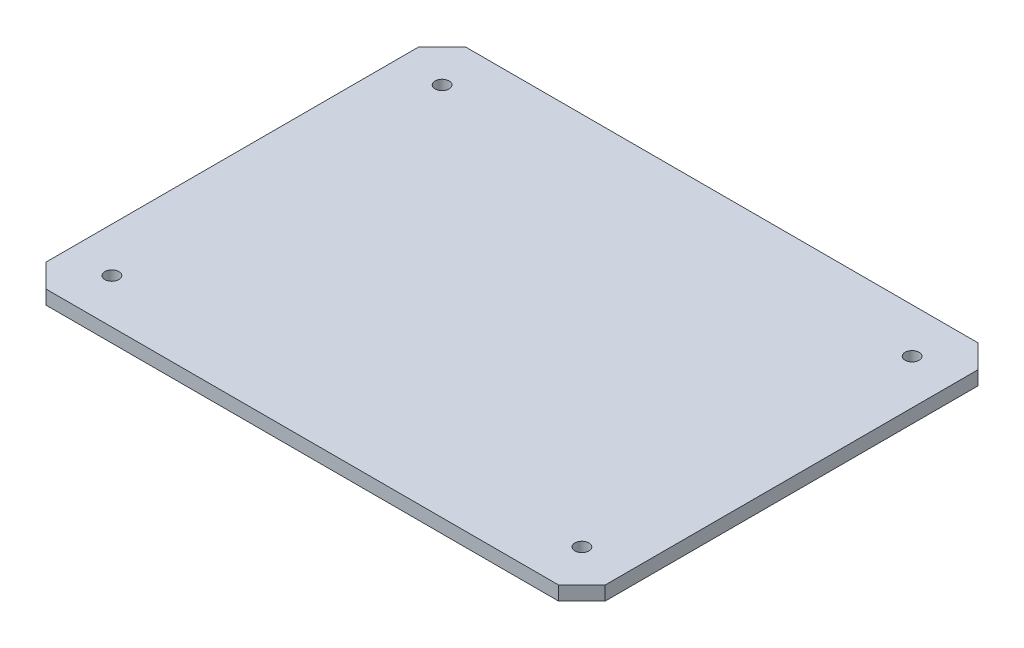
SolidWorks part; units mm, degrees
ref_plane "Front Plane" through (0, 0, 0) normal (0, 0, 1) x (1, 0, 0)
ref_plane "Top Plane" through (0, 0, 0) normal (0, 1, 0) x (1, 0, 0)
ref_plane "Right Plane" through (0, 0, 0) normal (1, 0, 0) x (0, 0, -1)
sketch "Sketch1" plane through (0, 0, 0) normal (0, 1, 0) x (1, 0, 0)
  line L1 (-60, 45) -> (60, 45)
  line L2 (-60, 45) -> (-60, -45)
  line L3 (-60, -45) -> (60, -45)
  line L4 (60, 45) -> (60, -45)
  line L5 (-60, 45) -> (60, -45) construction
  line L6 (-60, -45) -> (60, 45) construction
  point P0 (0, 0)
  dimension "D1" = 90
  dimension "D2" = 120
extrude "Boss-Extrude1" add sketch "Sketch1" along normal blind 3
chamfer "Chamfer1" distance 5 angle 45 4 edges at (-60, 1.5, 45) (-60, 1.5, -45) (60, 1.5, -45) (60, 1.5, 45)
sketch "Sketch5" plane through (0, 0, 0) normal (0, -1, 0) x (1, 0, 0)
  line L3 (-57.5, 42.5) -> (-6.9406, -8.0594) construction
  line L4 (-55, 45) -> (-60, 40) construction
  point P6 (-50.4289, 35.4289)
  point P16 (-52.9991, 39.1733)
  point P17 (-52.5503, 37.5503)
  dimension "D1" = 10
hole_wizard "Ø3.0 (3) Diameter Hole2" positions "Sketch5" profile "Sketch6" hole size "Ø3.0" standard "ANSI Metric" end condition through all
sketch "Sketch6" plane through (-50.4289, 0, 35.4289) normal (1, 0, 0) x (0, 0, -1)
  line L0 (0, 0) -> (0, 3)
  line L1 (0, 3) -> (1.5, 3)
  line L2 (1.5, 3) -> (1.5, 0)
  line L5 (1.5, 0) -> (0, 0)
  line L11 (0, -6.35) -> (0, 107.95) construction
  dimension "Thru Hole Dia." = 3
  dimension "Thru Hole Depth" = 3
mirror "Mirror1" about plane through (0, 0, 0) normal (0, 0, 1) of "Ø3.0 (3) Diameter Hole2" second plane through (0, 0, 0) second plane normal (1, 0, 0)
